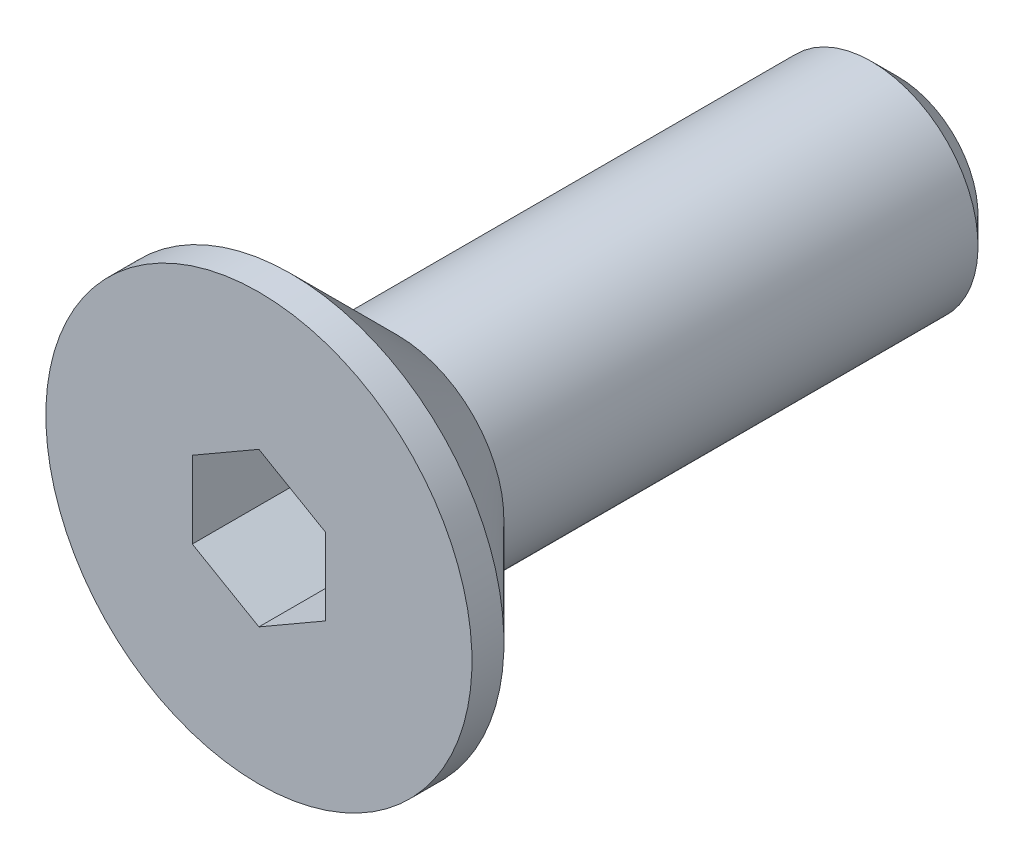
SolidWorks part; units mm, degrees
ref_plane "前视基准面" through (0, 0, 0) normal (0, 0, 1) x (1, 0, 0)
ref_plane "上视基准面" through (0, 0, 0) normal (0, 1, 0) x (1, 0, 0)
ref_plane "右视基准面" through (0, 0, 0) normal (1, 0, 0) x (0, 0, -1)
sketch "草图1" plane through (0, 0, 0) normal (1, 0, 0) x (0, 0, -1)
  line L0 (-6, 0) -> (-6, 4)
  line L1 (-6, 4) -> (-5.4, 4)
  line L2 (-5.4, 4) -> (-3.4, 2)
  line L3 (-3.4, 2) -> (6, 2)
  line L5 (6, 2) -> (6, 0)
  line L6 (6, 0) -> (-6, 0)
  dimension "D1" = 45
  dimension "D2" = 2
  dimension "D3" = 12
  dimension "D4" = 4
  dimension "D5" = 2.6
revolve "旋转1" add sketch "草图1" angle 360 about L6
chamfer "倒角1" distance 0.5 angle 45 1 edges at (0, 2, -6)
sketch "草图2" plane through (0, 0, 6) normal (0, 0, 1) x (1, 0, 0)
  line L1 (0, 1.4434) -> (-1.25, 0.7217)
  line L2 (-1.25, 0.7217) -> (-1.25, -0.7217)
  line L3 (-1.25, -0.7217) -> (0, -1.4434)
  line L4 (0, -1.4434) -> (1.25, -0.7217)
  line L5 (1.25, -0.7217) -> (1.25, 0.7217)
  line L6 (1.25, 0.7217) -> (0, 1.4434)
  circle A0 centre (0, 0) radius 1.25 construction
  dimension "D1" = 2.5
extrude "切除-拉伸1" cut sketch "草图2" against normal blind 2.5
